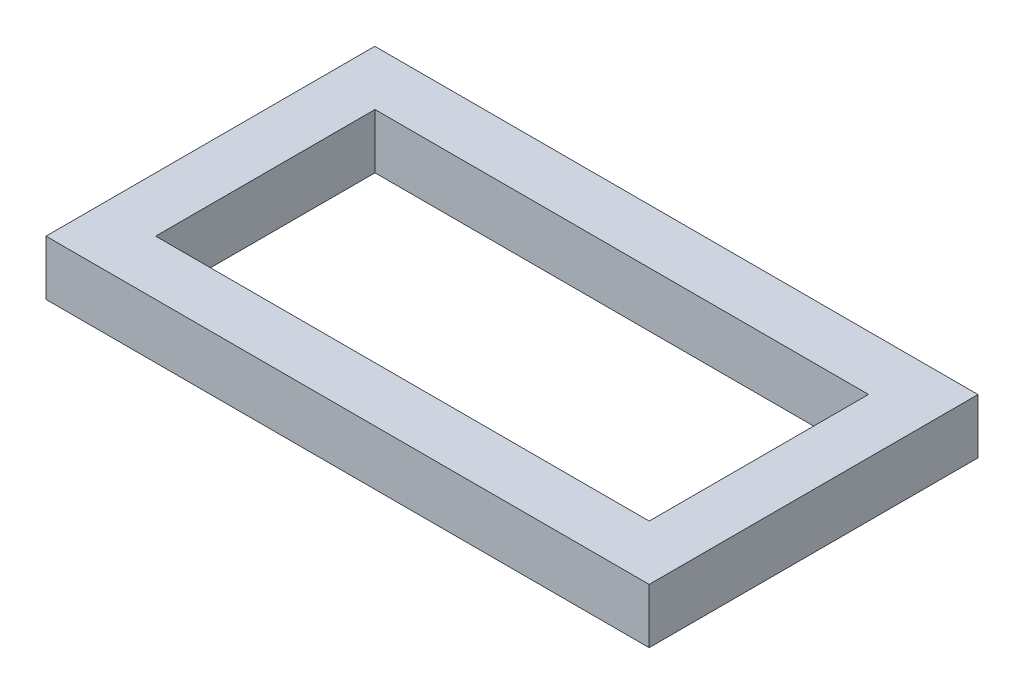
SolidWorks part; units mm, degrees
ref_plane "前视基准面" through (0, 0, 0) normal (0, 0, 1) x (1, 0, 0)
ref_plane "上视基准面" through (0, 0, 0) normal (0, 1, 0) x (1, 0, 0)
ref_plane "右视基准面" through (0, 0, 0) normal (1, 0, 0) x (0, 0, -1)
sketch "草图1" plane through (0, 0, 0) normal (0, 1, 0) x (1, 0, 0)
  line L0 (-90, 40) -> (90, 40)
  line L1 (-100, 50) -> (100, 50) construction
  line L2 (-100, 50) -> (-100, -50) construction
  line L3 (-100, -50) -> (100, -50) construction
  line L4 (100, 50) -> (100, -50) construction
  line L5 (-100, 50) -> (100, -50) construction
  line L6 (-100, -50) -> (100, 50) construction
  line L8 (-110, -40) -> (-110, -60)
  line L9 (-110, -60) -> (110, -60)
  line L10 (110, -40) -> (110, -60)
  line L11 (-110, -40) -> (110, -60) construction
  line L12 (-110, -60) -> (110, -40) construction
  line L14 (-110, 40) -> (-110, -40)
  line L16 (-90, 40) -> (-90, -40)
  line L17 (-110, 40) -> (-90, -40) construction
  line L18 (-110, -40) -> (-90, 40) construction
  line L20 (90, 40) -> (90, -40)
  line L22 (110, 40) -> (110, -40)
  line L23 (90, 40) -> (110, -40) construction
  line L24 (90, -40) -> (110, 40) construction
  line L25 (-110, 59.9317) -> (110, 59.9317)
  line L26 (-110, 59.9317) -> (-110, 40)
  line L28 (110, 59.9317) -> (110, 40)
  line L29 (-110, 59.9317) -> (110, 40) construction
  line L30 (-110, 40) -> (110, 59.9317) construction
  line L31 (-90, -40) -> (90, -40)
  point P0 (0, 0)
  point P6 (0, -50)
  point P11 (-100, 0)
  point P15 (100, 0)
  point P16 (0, 49.9659)
  dimension "D1" = 100
  dimension "D2" = 200
  dimension "D3" = 20
  dimension "D4" = 220
extrude "凸台-拉伸1" add sketch "草图1" against normal blind 20
